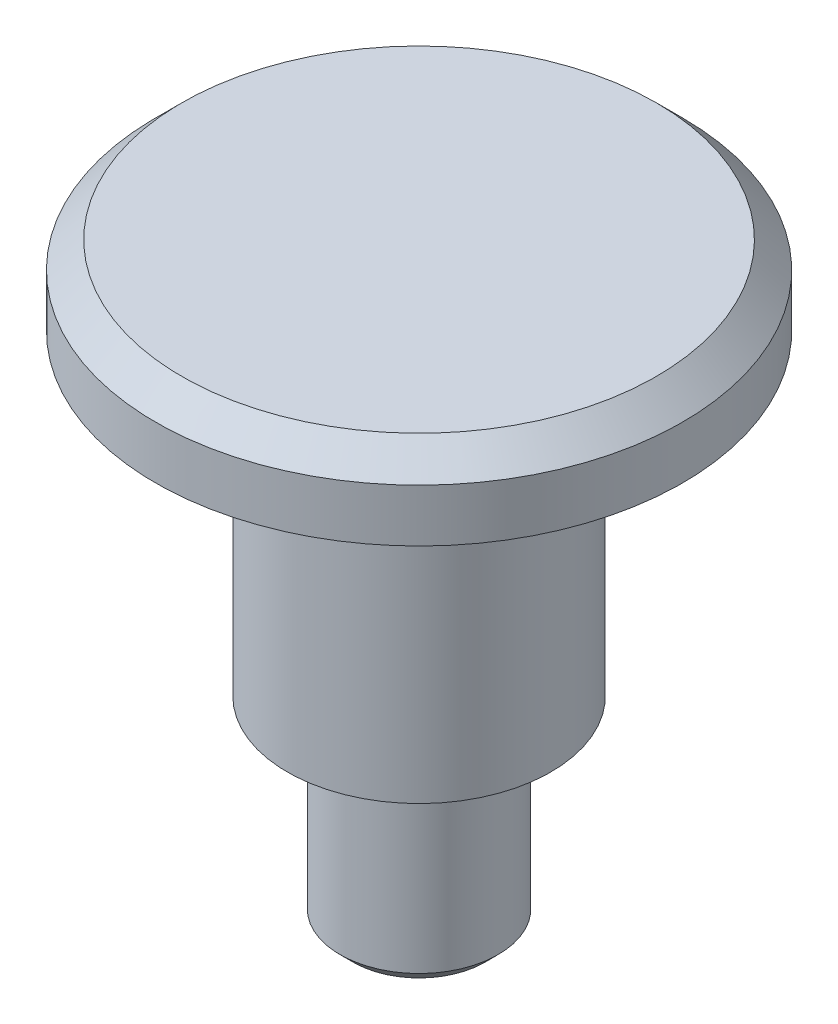
SolidWorks part; units mm, degrees
ref_plane "Plan1" through (0, 0, 0) normal (0, 0, 1) x (1, 0, 0)
ref_plane "Plan2" through (0, 0, 0) normal (0, 1, 0) x (1, 0, 0)
ref_plane "Plan3" through (0, 0, 0) normal (1, 0, 0) x (0, 0, -1)
sketch "Esquisse1" plane through (0, 0, 0) normal (0, 0, 1) x (1, 0, 0)
  line L0 (0, 0) -> (0, 100) construction
  line L1 (0, 0) -> (2.5, 0)
  line L2 (3, 0.5) -> (3, 7.5)
  line L3 (5, 7.5) -> (5, 19.5)
  line L4 (5.6, 19.5) -> (10, 19.5)
  line L5 (10, 21.5) -> (10, 19.5)
  line L7 (9, 22.5) -> (0, 22.5)
  line L8 (0, 22.5) -> (0, 0)
  line L9 (5, 7.5) -> (3.6, 7.5)
  line L10 (9, 22.5) -> (10, 21.5)
  line L11 (2.5, 0) -> (3, 0.5)
  arc A0 (3.6, 7.5) -> (3, 7.5) centre (3.3, 7.5) ccw
  arc A1 (5.6, 19.5) -> (5, 19.5) centre (5.3, 19.5) ccw
  point P3 (3, 0)
  dimension "D4" = 0.3
  dimension "D5" = 5
  dimension "D6" = 0.3
  dimension "D1" = 7.5
  dimension "D2" = 12
  dimension "D3" = 3
  dimension "D7" = 3
  dimension "D8" = 10
  dimension "D12" = 0.5
  dimension "D9" = 1
  dimension "D10" = 1
revolve "Base-Révolution" add sketch "Esquisse1" angle 360 about L0
